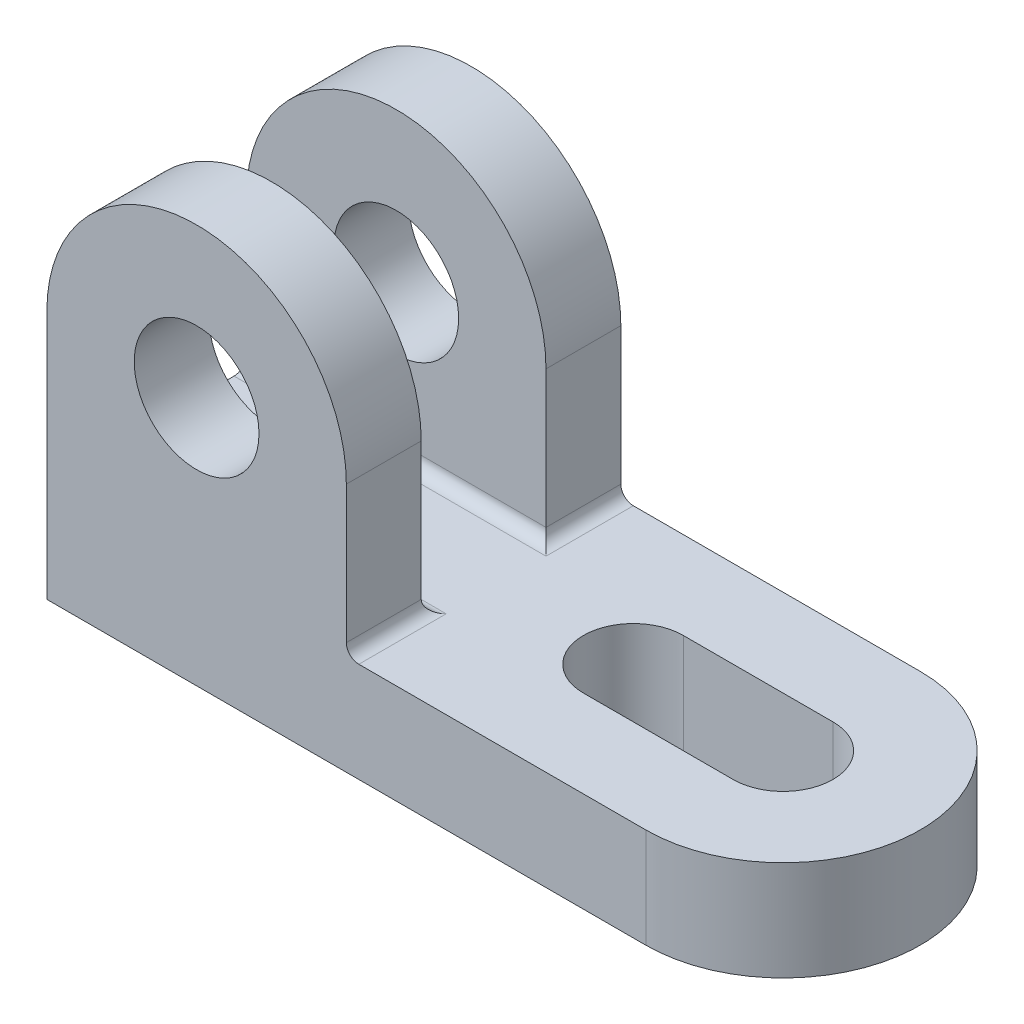
SolidWorks part; units mm, degrees
ref_plane "Front Plane" through (0, 0, 0) normal (0, 0, 1) x (1, 0, 0)
ref_plane "Top Plane" through (0, 0, 0) normal (0, 1, 0) x (1, 0, 0)
ref_plane "Right Plane" through (0, 0, 0) normal (1, 0, 0) x (0, 0, -1)
sketch "Sketch1" plane through (0, 0, 0) normal (0, 1, 0) x (1, 0, 0)
  line L1 (-59, 22) -> (37, 22)
  line L2 (-59, 22) -> (-59, -22)
  line L3 (-59, -22) -> (37, -22)
  line L5 (-59, 22) -> (59, -22) construction
  line L6 (-59, -22) -> (59, 22) construction
  arc A0 (37, -22) -> (37, 22) centre (37, 0) ccw
  point P1 (0, 0)
  dimension "D1" = 118
  dimension "D2" = 44
extrude "Boss-Extrude1" add sketch "Sketch1" along normal blind 16 contours A0 L1 L2 L3
sketch "Sketch2" plane through (0, 16, 0) normal (0, 1, 0) x (1, 0, 0)
  line L0 (37, 0) -> (13, 0) construction
  line L1 (37, -8) -> (13, -8)
  line L2 (37, 8) -> (13, 8)
  arc A0 (37, -8) -> (37, 8) centre (37, 0) ccw
  arc A1 (13, 8) -> (13, -8) centre (13, 0) ccw
  point P4 (25, 0)
  dimension "D1" = 8
  dimension "D2" = 24
extrude "Cut-Extrude1" cut sketch "Sketch2" against normal through all
sketch "Sketch3" plane through (0, 0, 22) normal (0, 0, 1) x (1, 0, 0)
  line L1 (-59, 0) -> (-11, 0)
  line L2 (-59, 0) -> (-59, 40)
  line L3 (-59, 40) -> (-11, 40)
  line L4 (-11, 0) -> (-11, 40)
  circle A0 centre (-35, 40) radius 24
  circle A1 centre (-35, 40) radius 10
  line M7 (37, 16) -> (-59, 16)
  dimension "D1" = 40
  dimension "D2" = 48
extrude "Boss-Extrude2" add sketch "Sketch3" against normal blind 12 contours A1 L3 A0 | A1 L3 A0 | A0 L2 M7 | A0 L4 M7
mirror "Mirror1" about plane through (0, 0, 0) normal (0, 0, 1) of "Boss-Extrude2"
fillet "Fillet1" radius 2 4 edges at (-11, 16, 16) (-35, 16, 10) (-11, 16, -16) (-35, 16, -10)
